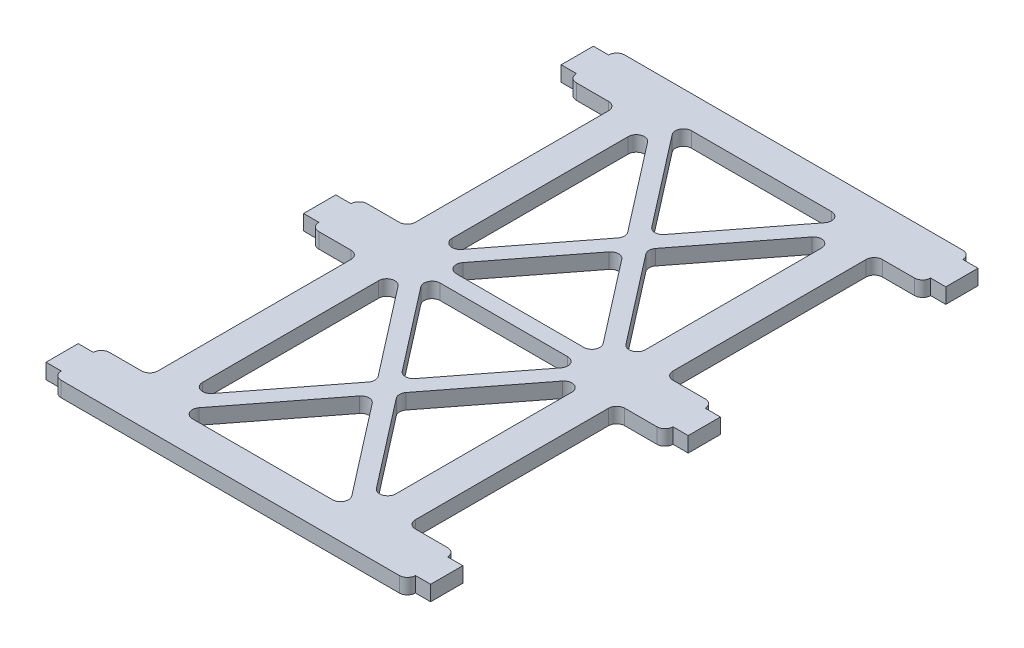
SolidWorks part; units mm, degrees
ref_plane "Front Plane" through (0, 0, 0) normal (0, 0, 1) x (1, 0, 0)
ref_plane "Top Plane" through (0, 0, 0) normal (0, 1, 0) x (1, 0, 0)
ref_plane "Right Plane" through (0, 0, 0) normal (1, 0, 0) x (0, 0, -1)
sketch "Sketch1" plane through (0, 34.29, 0) normal (0, 1, 0) x (1, 0, 0)
  line L0 (28.7528, 190.5) -> (31.75, 190.5) construction
  line L1 (0, -190.5) -> (0, 187.198) construction
  line L2 (38.1028, 187.198) -> (35.1028, 187.198) construction
  line L3 (35.1028, -190.5) -> (38.1, -190.5) construction
  line L5 (-25.4, 65.0875) -> (25.4, 65.0875)
  line L6 (-25.4, 65.0875) -> (-25.4, 176.2125)
  line L7 (-25.4, 176.2125) -> (25.4, 176.2125)
  line L8 (25.4, 65.0875) -> (25.4, 176.2125)
  line L9 (-25.4, 65.0875) -> (25.4, 176.2125) construction
  line L10 (-25.4, 176.2125) -> (25.4, 65.0875) construction
  point P0 (0, 120.65)
  dimension "D1" = 111.125
  dimension "D2" = 50.8
  dimension "D3" = 14.2875
extrude "Boss-Extrude1" add sketch "Sketch1" along normal mid plane 3 contours L7 L8 L5 L6
sketch "Sketch2" plane through (0, 35.79, 0) normal (0, 1, 0) x (1, 0, 0)
  line L0 (0, 176.2125) -> (0, 65.0186) construction
  line L1 (-25.4, 176.2125) -> (25.4, 176.2125) construction
  line L2 (25.4, 120.65) -> (-25.4, 120.65) construction
  line L3 (25.4, 65.0875) -> (25.4, 176.2125) construction
  line L4 (-25.4, 65.0875) -> (-25.4, 176.2125) construction
  line L5 (-34.925, 176.2125) -> (-25.4, 166.6875) construction
  line L6 (34.925, 166.6875) -> (25.4, 166.6875)
  line L7 (34.925, 166.6875) -> (34.925, 176.2125)
  line L8 (34.925, 176.2125) -> (25.4, 176.2125)
  line L9 (25.4, 166.6875) -> (25.4, 176.2125)
  line L10 (34.925, 166.6875) -> (25.4, 176.2125) construction
  line L11 (34.925, 176.2125) -> (25.4, 166.6875) construction
  line L12 (-34.925, 166.6875) -> (-25.4, 176.2125) construction
  line L13 (-25.4, 166.6875) -> (-25.4, 176.2125)
  line L14 (-34.925, 176.2125) -> (-25.4, 176.2125)
  line L15 (-34.925, 166.6875) -> (-34.925, 176.2125)
  line L16 (-34.925, 166.6875) -> (-25.4, 166.6875)
  line L17 (34.925, 115.8875) -> (25.4, 115.8875)
  line L18 (34.925, 115.8875) -> (34.925, 125.4125)
  line L19 (34.925, 125.4125) -> (25.4, 125.4125)
  line L20 (25.4, 115.8875) -> (25.4, 125.4125)
  line L21 (34.925, 115.8875) -> (25.4, 125.4125) construction
  line L22 (34.925, 125.4125) -> (25.4, 115.8875) construction
  line L23 (-25.4, 115.8875) -> (-25.4, 125.4125)
  line L24 (-34.925, 125.4125) -> (-25.4, 125.4125)
  line L25 (-34.925, 115.8875) -> (-34.925, 125.4125)
  line L26 (-34.925, 115.8875) -> (-25.4, 115.8875)
  line L27 (-34.925, 125.4125) -> (-25.4, 115.8875) construction
  line L28 (-34.925, 115.8875) -> (-25.4, 125.4125) construction
  line L29 (34.925, 65.0875) -> (25.4, 65.0875)
  line L30 (34.925, 65.0875) -> (34.925, 74.6125)
  line L31 (34.925, 74.6125) -> (25.4, 74.6125)
  line L32 (25.4, 65.0875) -> (25.4, 74.6125)
  line L33 (34.925, 65.0875) -> (25.4, 74.6125) construction
  line L34 (34.925, 74.6125) -> (25.4, 65.0875) construction
  line L35 (-25.4, 65.0875) -> (-25.4, 74.6125)
  line L36 (-34.925, 74.6125) -> (-25.4, 74.6125)
  line L37 (-34.925, 65.0875) -> (-34.925, 74.6125)
  line L38 (-34.925, 65.0875) -> (-25.4, 65.0875)
  line L39 (-34.925, 74.6125) -> (-25.4, 65.0875) construction
  line L40 (-34.925, 65.0875) -> (-25.4, 74.6125) construction
  point P11 (30.1625, 171.45)
  point P21 (-30.1625, 171.45)
  point P24 (30.1625, 120.65)
  point P33 (-30.1625, 120.65)
  point P34 (30.1625, 69.85)
  point P43 (-30.1625, 69.85)
  dimension "D1" = 9.525
  dimension "D2" = 9.525
  dimension "D3" = 3
extrude "Boss-Extrude2" add sketch "Sketch2" against normal up to surface (3 mm away) up to face at (0, 32.79, -120.65)
sketch "Sketch4" plane through (0, 35.79, 0) normal (0, 1, 0) x (1, 0, 0)
  line L0 (25.4, 125.4125) -> (25.4, 166.6875) construction
  line L1 (-19.05, 169.8625) -> (19.05, 169.8625)
  line L2 (-19.05, 169.8625) -> (-19.05, 71.4375)
  line L3 (-19.05, 71.4375) -> (19.05, 71.4375)
  line L4 (19.05, 169.8625) -> (19.05, 71.4375)
  line L5 (-19.05, 169.8625) -> (19.05, 71.4375) construction
  line L6 (-19.05, 71.4375) -> (19.05, 169.8625) construction
  line L7 (-25.4, 125.4125) -> (-25.4, 166.6875) construction
  line L8 (-34.925, 176.2125) -> (34.925, 176.2125) construction
  line L9 (-34.925, 65.0875) -> (34.925, 65.0875) construction
  line L10 (-19.05, 120.65) -> (19.05, 120.65) construction
  line L11 (19.05, 120.65) -> (-19.05, 169.8625) construction
  line L12 (19.05, 120.65) -> (-19.05, 71.4375) construction
  line L13 (-19.05, 120.65) -> (19.05, 169.8625) construction
  line L14 (19.05, 71.4375) -> (-19.05, 120.65) construction
  line L15 (-19.05, 119.0625) -> (19.05, 119.0625)
  line L16 (-19.05, 122.2375) -> (19.05, 122.2375)
  line L17 (20.3053, 72.4093) -> (-17.0423, 120.65)
  line L18 (-17.0423, 120.65) -> (20.3053, 168.8907)
  line L19 (21.0577, 120.65) -> (-17.7947, 70.4657)
  line L20 (21.0577, 120.65) -> (-17.7947, 170.8343)
  line L21 (17.7947, 70.4657) -> (-21.0577, 120.65)
  line L22 (-21.0577, 120.65) -> (17.7947, 170.8343)
  line L23 (17.0423, 120.65) -> (-20.3053, 72.4093)
  line L24 (17.0423, 120.65) -> (-20.3053, 168.8907)
  point P0 (0, 120.65)
  dimension "D1" = 6.35
  dimension "D2" = 6.35
  dimension "D3" = 6.35
  dimension "D4" = 6.35
  dimension "D5" = 1.5875
  dimension "D6" = 1.5875
  dimension "D7" = 1.5875
  dimension "D8" = 1.5875
extrude "Cut-Extrude1" cut sketch "Sketch4" against normal blind 3 contours L15 L19 L17 L4 | L3 L21 L19 | L23 L21 L15 L2 | L23 L15 L17 | L16 L24 L18 | L20 L16 L4 L18 | L20 L22 L1 | L22 L24 L2 L16
fillet "Fillet1" radius 1.5875 44 edges at (-15.8133, 34.29, -119.0625) (15.8133, 34.29, -119.0625) (0, 34.29, -98.637) (-19.05, 34.29, -118.0568) (-2.0077, 34.29, -96.0438) (-19.05, 34.29, -74.0307) (19.05, 34.29, -167.2693) (19.05, 34.29, -123.2432) (2.0077, 34.29, -145.2563) (17.0423, 34.29, -169.8625) (0, 34.29, -147.8495) (-17.0423, 34.29, -169.8625) (2.0077, 34.29, -96.0438) (19.05, 34.29, -118.0568) (19.05, 34.29, -74.0307) (34.925, 34.29, -65.0875) (34.925, 34.29, -74.6125) (25.4, 34.29, -74.6125) (25.4, 34.29, -115.8875) (34.925, 34.29, -115.8875) (34.925, 34.29, -125.4125) (25.4, 34.29, -125.4125) (25.4, 34.29, -166.6875) (34.925, 34.29, -166.6875) (34.925, 34.29, -176.2125) (-34.925, 34.29, -166.6875) (-25.4, 34.29, -166.6875) (-25.4, 34.29, -125.4125) (-34.925, 34.29, -125.4125) (-34.925, 34.29, -115.8875) (-25.4, 34.29, -115.8875) (-25.4, 34.29, -74.6125) (-34.925, 34.29, -74.6125) (-34.925, 34.29, -65.0875) (-19.05, 34.29, -123.2432) (-19.05, 34.29, -167.2693) (-2.0077, 34.29, -145.2563) (-17.0423, 34.29, -71.4375) (0, 34.29, -93.4505) (17.0423, 34.29, -71.4375) (-15.8133, 34.29, -122.2375) (0, 34.29, -142.663) (15.8133, 34.29, -122.2375) (-34.925, 34.29, -176.2125)
sketch "Sketch5" plane through (0, 35.79, 0) normal (0, 1, 0) x (1, 0, 0)
  line L0 (34.925, 168.275) -> (34.925, 174.625) construction
  line L1 (37.925, 168.275) -> (34.925, 168.275)
  line L2 (37.925, 168.275) -> (37.925, 174.625)
  line L3 (37.925, 174.625) -> (34.925, 174.625)
  line L4 (34.925, 168.275) -> (34.925, 174.625)
  line L5 (37.925, 168.275) -> (34.925, 174.625) construction
  line L6 (37.925, 174.625) -> (34.925, 168.275) construction
  line L7 (34.925, 168.275) -> (34.925, 174.625) construction
  line L8 (34.925, 171.45) -> (36.425, 171.45) construction
  line L9 (0, 196.0278) -> (0, 0) construction
  line L10 (-34.925, 171.45) -> (-36.425, 171.45) construction
  line L11 (-37.925, 174.625) -> (-34.925, 168.275) construction
  line L12 (-37.925, 168.275) -> (-34.925, 174.625) construction
  line L13 (-34.925, 168.275) -> (-34.925, 174.625)
  line L14 (-37.925, 174.625) -> (-34.925, 174.625)
  line L15 (-37.925, 168.275) -> (-37.925, 174.625)
  line L16 (-37.925, 168.275) -> (-34.925, 168.275)
  line L17 (37.925, 117.475) -> (34.925, 117.475)
  line L18 (37.925, 117.475) -> (37.925, 123.825)
  line L19 (37.925, 123.825) -> (34.925, 123.825)
  line L20 (34.925, 117.475) -> (34.925, 123.825)
  line L21 (37.925, 117.475) -> (34.925, 123.825) construction
  line L22 (37.925, 123.825) -> (34.925, 117.475) construction
  line L23 (34.925, 120.65) -> (36.425, 120.65) construction
  line L24 (-34.925, 117.475) -> (-34.925, 123.825)
  line L25 (-37.925, 123.825) -> (-34.925, 123.825)
  line L26 (-37.925, 117.475) -> (-37.925, 123.825)
  line L27 (-37.925, 117.475) -> (-34.925, 117.475)
  line L28 (-34.925, 120.65) -> (-36.425, 120.65) construction
  line L29 (-37.925, 123.825) -> (-34.925, 117.475) construction
  line L30 (-37.925, 117.475) -> (-34.925, 123.825) construction
  line L31 (37.925, 66.675) -> (34.925, 66.675)
  line L32 (37.925, 66.675) -> (37.925, 73.025)
  line L33 (37.925, 73.025) -> (34.925, 73.025)
  line L34 (34.925, 66.675) -> (34.925, 73.025)
  line L35 (37.925, 66.675) -> (34.925, 73.025) construction
  line L36 (37.925, 73.025) -> (34.925, 66.675) construction
  line L37 (34.925, 69.85) -> (36.425, 69.85) construction
  line L38 (-34.925, 66.675) -> (-34.925, 73.025)
  line L39 (-37.925, 73.025) -> (-34.925, 73.025)
  line L40 (-37.925, 66.675) -> (-37.925, 73.025)
  line L41 (-37.925, 66.675) -> (-34.925, 66.675)
  line L42 (-34.925, 69.85) -> (-36.425, 69.85) construction
  line L43 (-37.925, 73.025) -> (-34.925, 66.675) construction
  line L44 (-37.925, 66.675) -> (-34.925, 73.025) construction
  line L45 (-36.425, 171.45) -> (-36.425, 120.65) construction
  point P0 (36.425, 171.45)
  point P7 (36.425, 120.65)
  point P21 (-36.425, 171.45)
  point P35 (-36.425, 120.65)
  point P36 (36.425, 69.85)
  point P49 (-36.425, 69.85)
  dimension "D1" = 3
  dimension "D2" = 6.35
  dimension "D4" = 50.8
  dimension "D3" = 3
extrude "Boss-Extrude3" add sketch "Sketch5" against normal up to surface (3 mm away) up to face at (0, 32.79, -129.3309)
